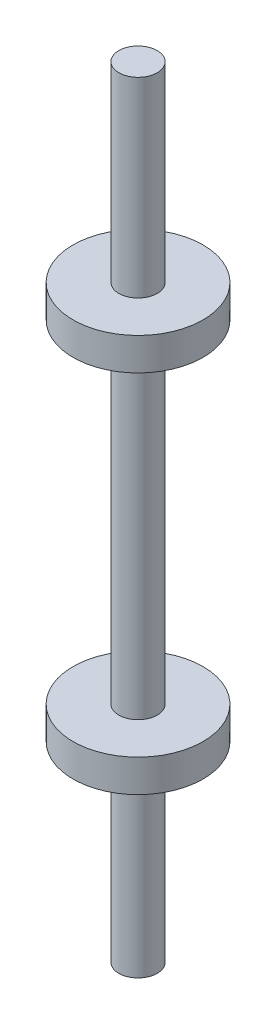
SolidWorks part; units mm, degrees
ref_plane "Front Plane" through (0, 0, 0) normal (0, 0, 1) x (1, 0, 0)
ref_plane "Top Plane" through (0, 0, 0) normal (0, 1, 0) x (1, 0, 0)
ref_plane "Right Plane" through (0, 0, 0) normal (1, 0, 0) x (0, 0, -1)
sketch "Sketch1" plane through (0, 0, 0) normal (0, 1, 0) x (1, 0, 0)
  circle A0 centre (0, 0) radius 7.5
  dimension "D1" = 15
extrude "Boss-Extrude1" add sketch "Sketch1" along normal blind 304.8
sketch "Sketch2" plane through (0, 0, 0) normal (0, 0, 1) x (1, 0, 0)
  line L0 (0, -8.25) -> (0, 8.25) construction
  line L1 (0, 217.4) -> (25.4, 217.4)
  line L2 (0, 217.4) -> (0, 230.1)
  line L3 (0, 230.1) -> (25.4, 230.1)
  line L4 (25.4, 217.4) -> (25.4, 230.1)
  line L6 (0, 87.4) -> (25.4, 87.4)
  line L7 (0, 87.4) -> (0, 74.7)
  line L8 (0, 74.7) -> (25.4, 74.7)
  line L9 (25.4, 87.4) -> (25.4, 74.7)
  line L10 (0, 74.7) -> (0, 0) construction
  line L11 (0, 304.8) -> (0, 230.1) construction
  line L12 (7.5, 304.8) -> (-7.5, 304.8) construction
  dimension "D1" = 130
  dimension "D2" = 25.4
  dimension "D3" = 25.4
  dimension "D4" = 12.7
revolve "Revolve1" add sketch "Sketch2" angle 360 about L2
